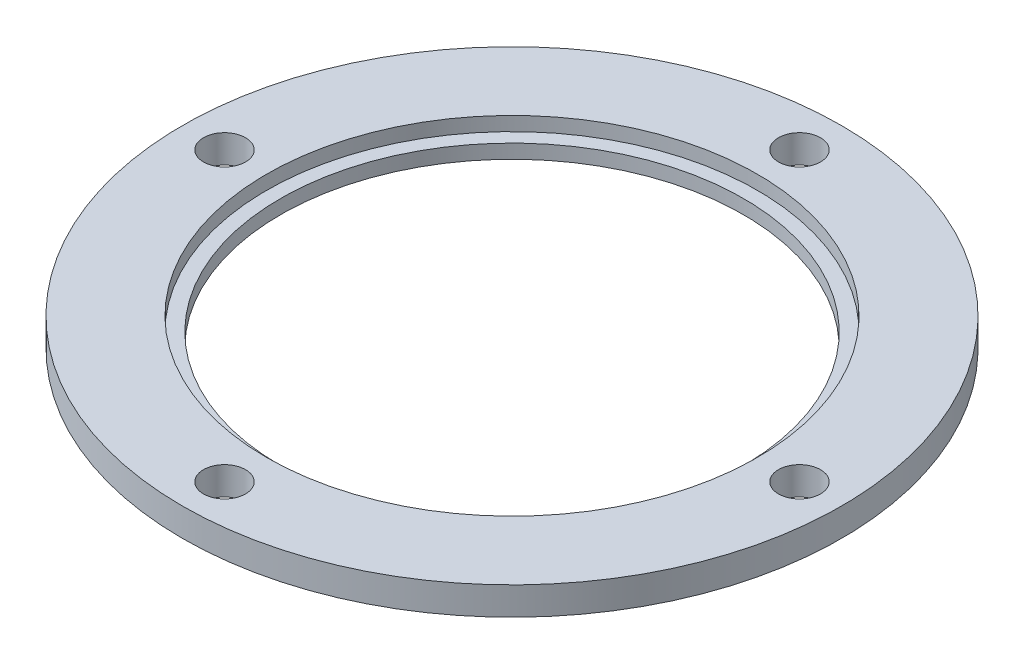
SolidWorks part; units mm, degrees
material "6060 合金"
ref_plane "前视基准面" through (0, 0, 0) normal (0, 0, 1) x (1, 0, 0)
ref_plane "上视基准面" through (0, 0, 0) normal (0, 1, 0) x (1, 0, 0)
ref_plane "右视基准面" through (0, 0, 0) normal (1, 0, 0) x (0, 0, -1)
other "Configuration Table"
sketch "草图1" plane through (0, 0, 0) normal (0, 1, 0) x (1, 0, 0)
  circle A0 centre (0, 0) radius 16.5
  circle A1 centre (0, 0) radius 17.5
  circle A2 centre (0, 0) radius 23.5
  dimension "D1" = 35
  dimension "D2" = 1
  dimension "D3" = 6
extrude "凸台-拉伸1" add sketch "草图1" along normal blind 1 contours A2 A1 | A1 A0
sketch "草图2" plane through (0, 1, 0) normal (0, 1, 0) x (1, 0, 0)
  circle A0 centre (0, 0) radius 17.5
  circle A1 centre (0, 0) radius 23.5
  circle A2 centre (0, 0) radius 23.5
  dimension "D2" = 6
  dimension "D1" = 0
extrude "凸台-拉伸2" add sketch "草图2" along normal blind 1
sketch "草图3" plane through (0, 2, 0) normal (0, 1, 0) x (1, 0, 0)
  circle A0 centre (0, 0) radius 20.5 construction
  circle A1 centre (0, 0) radius 23.5 construction
  circle A2 centre (0, 20.5) radius 1.5
  circle A3 centre (20.5, 0) radius 1.5
  circle A4 centre (0, -20.5) radius 1.5
  circle A5 centre (-20.5, 0) radius 1.5
  dimension "D1" = 3
  dimension "D2" = 3
  dimension "D3" = 4
extrude "切除-拉伸1" cut sketch "草图3" against normal blind 11
